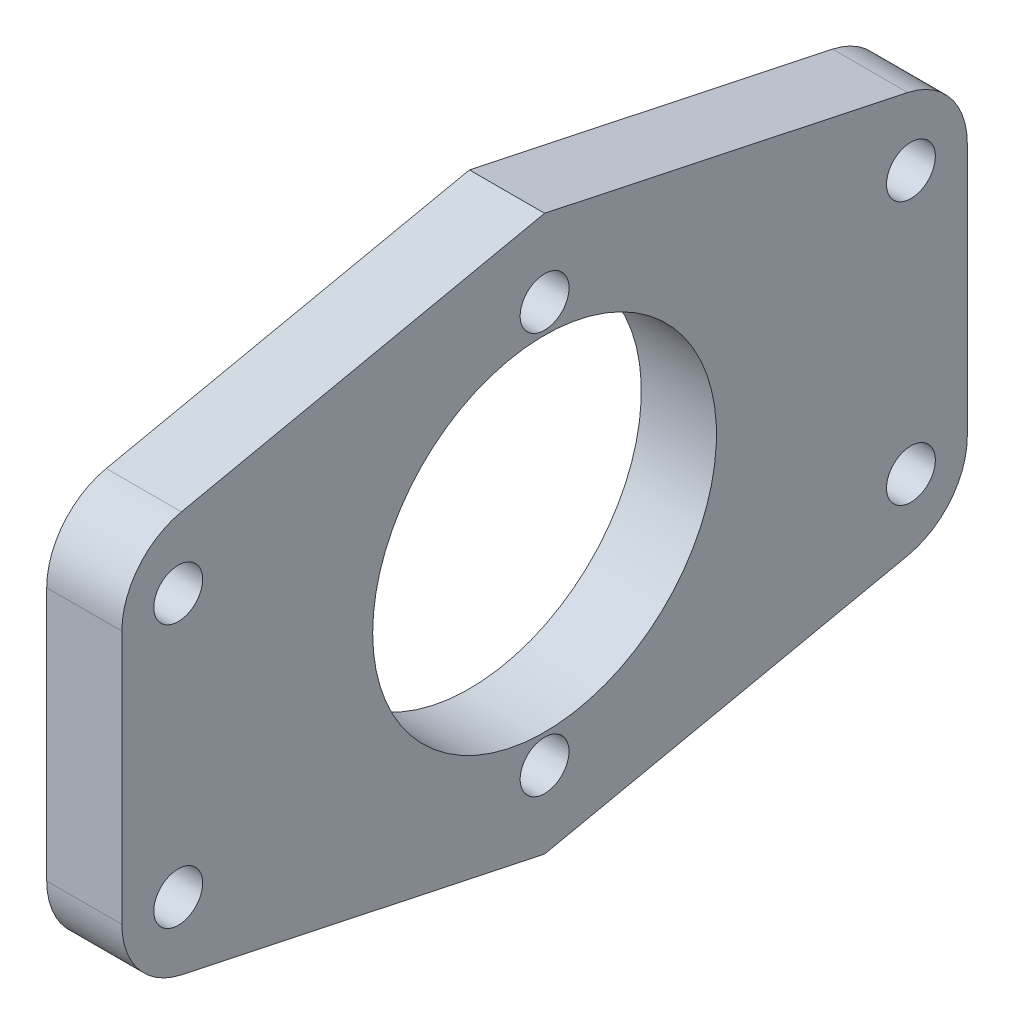
SolidWorks part; units mm, degrees
ref_plane "Front" through (0, 0, 0) normal (0, 0, 1) x (1, 0, 0)
ref_plane "Top" through (0, 0, 0) normal (0, 1, 0) x (1, 0, 0)
ref_plane "Right" through (0, 0, 0) normal (1, 0, 0) x (0, 0, -1)
sketch "Sketch1" plane through (0, 0, 0) normal (1, 0, 0) x (0, 0, -1)
  line L0 (45, 0) -> (22.5, 4.7697)
  line L1 (0, 0) -> (45, 0)
  line L2 (0, 0) -> (0, -20)
  line L3 (0, -20) -> (45, -20)
  line L4 (45, 0) -> (45, -20)
  line L5 (22.5, 4.7697) -> (0, 0)
  line L6 (0, -20) -> (22.5, -24.7697)
  line L7 (22.5, -24.7697) -> (45, -20)
  circle A0 centre (22.5, 0.6808) radius 1.3
  circle A1 centre (22.5, -20.6808) radius 1.3
  circle A2 centre (42, -3) radius 1.3
  circle A3 centre (3, -3) radius 1.3
  circle A4 centre (3, -17) radius 1.3
  circle A5 centre (42, -17) radius 1.3
  dimension "D7" = 2.6
  dimension "D8" = 2.6
  dimension "D13" = 2.6
  dimension "D1" = 45
  dimension "D2" = 20
  dimension "D3" = 23
  dimension "D4" = 23
  dimension "D5" = 23
  dimension "D6" = 23
  dimension "D9" = 4
  dimension "D10" = 4
  dimension "D11" = 4
  dimension "D12" = 4
  dimension "D14" = 3
  dimension "D15" = 3
  dimension "D16" = 2
  dimension "D17" = 2
extrude "Boss-Extrude1" add sketch "Sketch1" along normal blind 4 contours L4 L1 L2 L3 | L0 L5 L1 A0 | L6 L7 L3 A1
sketch "Sketch2" plane through (0, 0, 0) normal (-1, 0, 0) x (0, 0, 1)
  line L0 (-45, 0) -> (-45, -20) construction
  circle A0 centre (-22.5, -10) radius 9.15
  dimension "D1" = 18.3
  dimension "D2" = 22.5
  dimension "D3" = 10
extrude "Cut-Extrude1" cut sketch "Sketch2" against normal through all
fillet "Fillet1" radius 4 4 edges at (2, 0, 0) (2, 0, -45) (2, -20, -45) (2, -20, 0)
